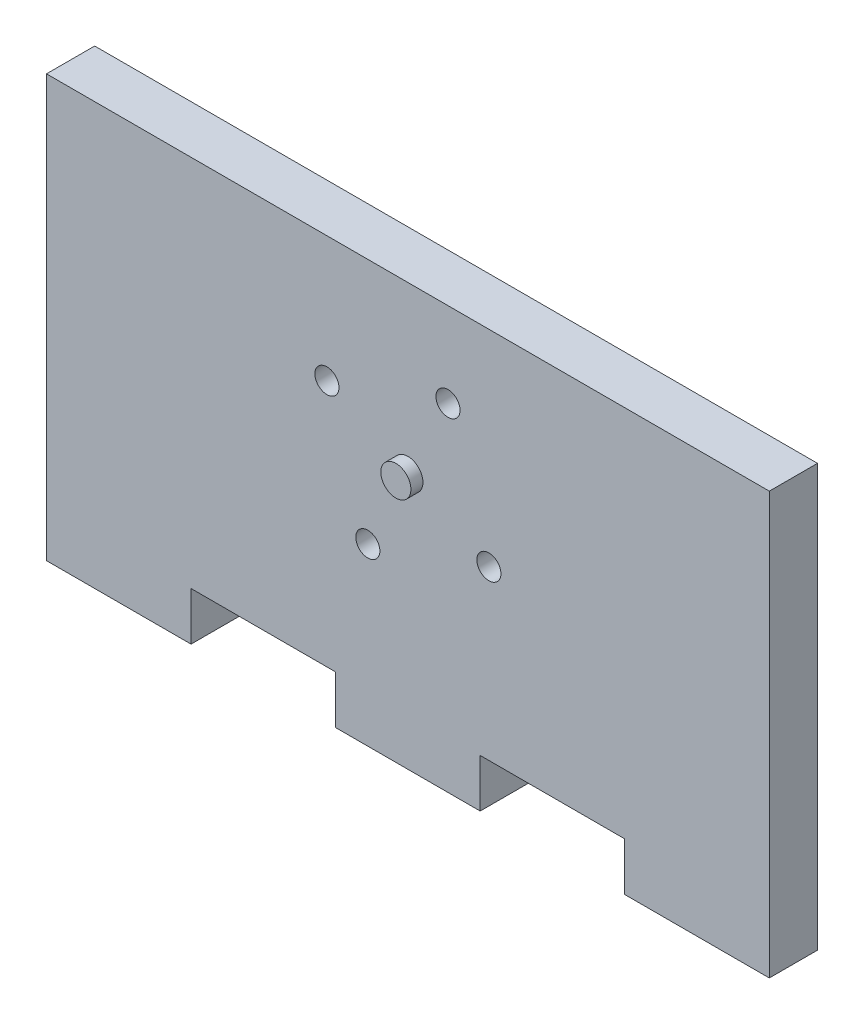
SolidWorks part; units mm, degrees
ref_plane "Front Plane" through (0, 0, 0) normal (0, 0, 1) x (1, 0, 0)
ref_plane "Top Plane" through (0, 0, 0) normal (0, 1, 0) x (1, 0, 0)
ref_plane "Right Plane" through (0, 0, 0) normal (1, 0, 0) x (0, 0, -1)
sketch "Sketch1" plane through (0, 0, 0) normal (0, 0, 1) x (1, 0, 0)
  line L1 (38.1, -22.225) -> (-38.1, -22.225)
  line L2 (38.1, -22.225) -> (38.1, 22.225)
  line L3 (38.1, 22.225) -> (-38.1, 22.225)
  line L4 (-38.1, -22.225) -> (-38.1, 22.225)
  line L5 (38.1, -22.225) -> (-38.1, 22.225) construction
  line L6 (38.1, 22.225) -> (-38.1, -22.225) construction
  point P0 (0, 0)
  dimension "D1" = 76.2
  dimension "D2" = 44.45
extrude "Boss-Extrude1" add sketch "Sketch1" along normal blind 5.08
sketch "Sketch2" plane through (0, 0, 0) normal (0, 0, -1) x (-1, 0, 0)
  circle A0 centre (0, 4.7625) radius 1.5875
extrude "Boss-Extrude6" add sketch "Sketch2" against normal blind 6.35
sketch "Sketch3" plane through (0, 0, 0) normal (0, 0, -1) x (-1, 0, 0)
  circle A0 centre (4.226, -3.7737) radius 1.27
  circle A1 centre (-8.5362, 0.5365) radius 1.27
  circle A2 centre (-4.226, 13.2987) radius 1.27
  circle A3 centre (8.5362, 8.9885) radius 1.27
extrude "Cut-Extrude1" cut sketch "Sketch3" against normal blind 6.35
sketch "Sketch4" plane through (0, -22.225, 0) normal (0, -1, 0) x (-1, 0, 0)
  line L0 (38.1, 0) -> (-38.1, 0) construction
  line L5 (22.86, 0) -> (7.62, 0)
  line L6 (22.86, 0) -> (22.86, -5.08)
  line L7 (22.86, -5.08) -> (7.62, -5.08)
  line L8 (7.62, 0) -> (7.62, -5.08)
  line L9 (38.1, -5.08) -> (-38.1, -5.08) construction
  line L10 (38.1, -5.08) -> (22.86, -5.08) construction
  line L11 (7.62, -5.08) -> (-7.62, -5.08) construction
  line L12 (-22.86, -5.08) -> (-38.1, -5.08) construction
  line L13 (-7.62, -5.08) -> (-22.86, -5.08)
  line L14 (-7.62, -5.08) -> (-7.62, 0)
  line L15 (-7.62, 0) -> (-22.86, 0)
  line L16 (-22.86, -5.08) -> (-22.86, 0)
extrude "Cut-Extrude2" cut sketch "Sketch4" against normal blind 5.08
equation "\"foamcore\"= .1in"
equation "\"MDF\"= .2in"
equation "\"GMaterial\"= \"MDF\""
equation "\"D1@Cut-Extrude2\"=\"GMaterial\""
equation "\"D1@Boss-Extrude1\"=\"GMaterial\""
